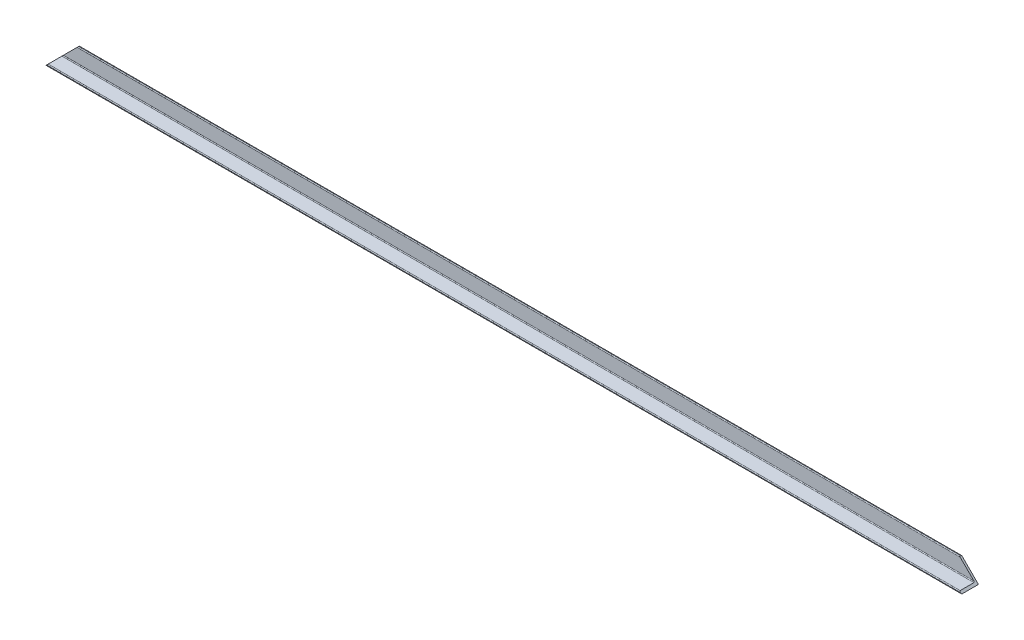
SolidWorks part; units mm, degrees
ref_plane "Front Plane" through (0, 0, 0) normal (0, 0, 1) x (1, 0, 0)
ref_plane "Top Plane" through (0, 0, 0) normal (0, 1, 0) x (1, 0, 0)
ref_plane "Right Plane" through (0, 0, 0) normal (1, 0, 0) x (0, 0, -1)
sketch "Sketch1" plane through (0, 0, 0) normal (0, 1, 0) x (1, 0, 0)
  line L1 (-610, 11.25) -> (610, 11.25)
  line L2 (-610, 11.25) -> (-610, -11.25)
  line L3 (-610, -11.25) -> (610, -11.25)
  line L4 (610, 11.25) -> (610, -11.25)
  line L5 (-610, 11.25) -> (610, -11.25) construction
  line L6 (-610, -11.25) -> (610, 11.25) construction
  point P0 (0, 0)
  dimension "D1" = 1220
  dimension "D2" = 22.5
extrude "Boss-Extrude1" add sketch "Sketch1" along normal blind 2.5
sketch "Sketch2" plane through (0, 2.5, 0) normal (0, 1, 0) x (1, 0, 0)
  line L0 (610, -11.25) -> (610, 11.25) construction
  line L1 (-610, 11.25) -> (610, 11.25)
  line L2 (-610, 11.25) -> (-610, 8.75)
  line L3 (-610, 8.75) -> (610, 8.75)
  line L4 (610, 11.25) -> (610, 8.75)
  dimension "D1" = 2.5
extrude "Boss-Extrude2" add sketch "Sketch2" along normal blind 20
sketch "Sketch3" plane through (0, 0, -8.75) normal (0, 0, 1) x (1, 0, 0)
  line L0 (-610, 22.5) -> (-610, -7.5)
  line L1 (-610, 22.5) -> (610, 22.5) construction
  line L2 (-610, -7.5) -> (-580, 22.5)
  line L3 (-580, 22.5) -> (-610, 22.5)
  line L4 (610, 22.5) -> (610, -7.5)
  line L5 (610, -7.5) -> (580, 22.5)
  line L6 (580, 22.5) -> (610, 22.5)
  dimension "D1" = 30
  dimension "D2" = 30
  dimension "D3" = 45
  dimension "D4" = 45
extrude "Cut-Extrude1" cut sketch "Sketch3" against normal blind 25 and the other way through all
fillet "Fillet2" radius 1 6 edges at (0, 0, -11.25) (0, 0, 11.25) (0, 2.5, 11.25) (0, 22.5, -11.25) (0, 22.5, -8.75) (0, 2.5, -8.75)
